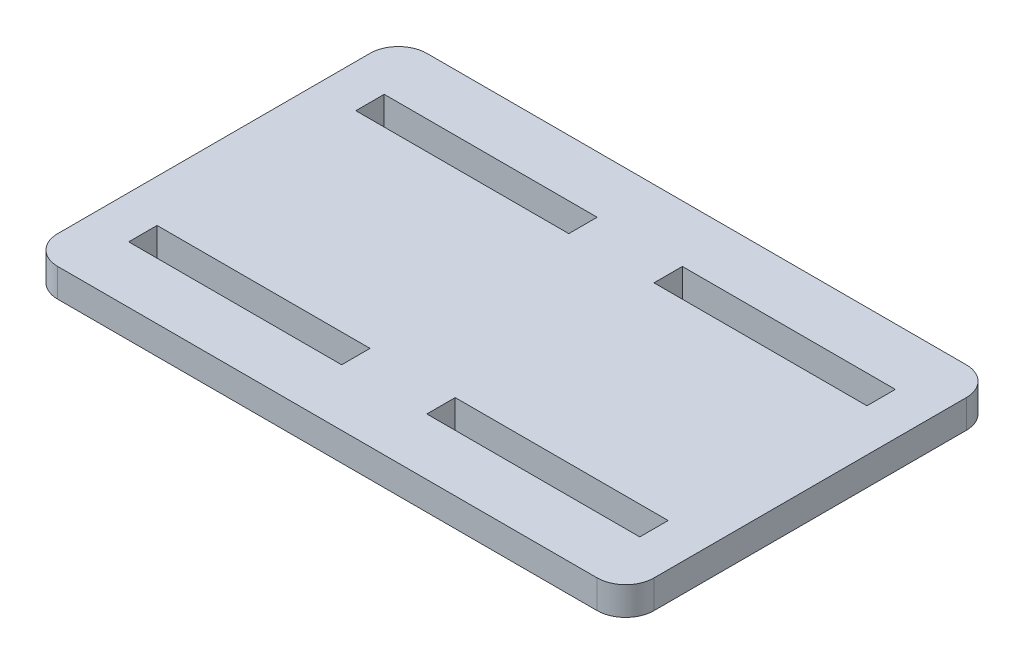
SolidWorks part; units mm, degrees
ref_plane "Front Plane" through (0, 0, 0) normal (0, 0, 1) x (1, 0, 0)
ref_plane "Top Plane" through (0, 0, 0) normal (0, 1, 0) x (1, 0, 0)
ref_plane "Right Plane" through (0, 0, 0) normal (1, 0, 0) x (0, 0, -1)
sketch "Sketch1" plane through (0, 0, 0) normal (1, 0, 0) x (0, 0, -1)
  line L0 (8.89, 0) -> (8.89, 2.54)
  line L1 (-8.89, 0) -> (-8.89, 2.54)
  line L2 (-8.89, 2.54) -> (8.89, 2.54)
  line L3 (-8.89, 0) -> (8.89, 0)
  point P0 (0, 0)
  dimension "D1" = 17.78
  dimension "D2" = 2.54
  dimension "D3" = 2.54
extrude "Boss-Extrude1" add sketch "Sketch1" along normal blind 11.43 contours L1 L3 L0 L2
sketch "Sketch2" plane through (0, 0, 0) normal (-1, 0, 0) x (0, 0, 1)
  line L0 (8.89, 0) -> (8.89, 2.54) construction
  line L1 (-8.89, 2.54) -> (8.89, 2.54)
  line L2 (-8.89, 2.54) -> (-8.89, 0)
  line L3 (-8.89, 0) -> (8.89, 0)
  line L4 (8.89, 2.54) -> (8.89, 0)
  dimension "D1" = 2.54
extrude "Boss-Extrude2" add sketch "Sketch2" along normal blind 15.24
mirror "Mirror1" about plane through (-15.24, 0, 0) normal (-1, 0, 0) of bodies 102 103
ref_plane "Plane1" through (11.43, 2.54, 8.89) normal (-1, 0, 0) x (0, 0, 1)
sketch "Sketch6" plane through (0, 0, -8.89) normal (0, 0, -1) x (-1, 0, 0)
  line L0 (41.91, 0) -> (41.91, 2.54) construction
  line L1 (-11.43, 2.54) -> (41.91, 2.54)
  line L2 (-11.43, 2.54) -> (-11.43, 0)
  line L3 (-11.43, 0) -> (41.91, 0)
  line L4 (41.91, 2.54) -> (41.91, 0)
  dimension "D1" = 2.54
sketch "Sketch7" plane through (0, 0, 8.89) normal (0, 0, 1) x (1, 0, 0)
  line L0 (11.43, 17.2085) -> (11.43, -12.1285) construction
  line L1 (-41.91, 2.54) -> (11.43, 2.54)
  line L2 (-41.91, 2.54) -> (-41.91, 0)
  line L3 (-41.91, 0) -> (11.43, 0)
  line L4 (11.43, 2.54) -> (11.43, 0)
  dimension "D1" = 2.54
ref_plane "Plane2" through (-15.24, 0, 0) normal (-1, 0, 0) x (0, 0, 1)
sketch "Sketch16" plane through (0, 0, 8.89) normal (0, 0, 1) x (1, 0, 0)
  line L0 (11.43, 0) -> (-41.91, 0) construction
  line L1 (-41.91, 2.54) -> (-38.1, 2.54)
  line L2 (-41.91, 2.54) -> (-41.91, 0)
  line L3 (-41.91, 0) -> (-38.1, 0)
  line L4 (-38.1, 2.54) -> (-38.1, 0)
  line L5 (11.43, 2.54) -> (-41.91, 2.54) construction
  line L6 (-15.24, 0) -> (-19.05, 0)
  line L7 (-15.24, 0) -> (-15.24, 2.54)
  line L8 (-15.24, 2.54) -> (-19.05, 2.54)
  line L9 (-19.05, 0) -> (-19.05, 2.54)
  line M3 (11.43, 2.54) -> (-41.91, 2.54)
  line M5 (-41.91, 0) -> (11.43, 0)
  dimension "D1" = 3.81
  dimension "D2" = 3.81
extrude "Boss-Extrude10" add sketch "Sketch16" along normal blind 7.62 contours L9 L7 M5 M3 | L4 L3 L2 L1
sketch "Sketch17" plane through (-19.05, 0, 0) normal (-1, 0, 0) x (0, 0, 1)
  line L0 (16.51, 2.54) -> (8.89, 2.54) construction
  line L1 (16.51, 0) -> (11.43, 0)
  line L2 (16.51, 0) -> (16.51, 2.54)
  line L3 (16.51, 2.54) -> (11.43, 2.54)
  line L4 (11.43, 0) -> (11.43, 2.54)
  dimension "D1" = 5.08
extrude "Boss-Extrude11" add sketch "Sketch17" along normal up to next
mirror "Mirror2" about plane through (-15.24, 0, 0) normal (-1, 0, 0) of "Boss-Extrude11", "Boss-Extrude10"
mirror "Mirror3" about plane through (0, 0, 0) normal (0, 0, 1) of "Mirror2", "Boss-Extrude11", "Boss-Extrude10"
sketch "Sketch18" plane through (0, 0, 0) normal (0, -1, 0) x (1, 0, 0)
  line L1 (-15.24, 8.89) -> (-10.2235, 8.89)
  line L2 (-15.24, 8.89) -> (-15.24, -8.89)
  line L3 (-15.24, -8.89) -> (-10.2235, -8.89)
  line L4 (-10.2235, 8.89) -> (-10.2235, -8.89)
  line L5 (11.43, -8.89) -> (-41.91, -8.89) construction
  line L7 (-15.24, 1.397) -> (-15.24, -1.397) construction
  dimension "D1" = 5.0165
  dimension "D2" = 17.78
fillet "Fillet1" radius 2.54 4 edges at (-41.91, 1.27, -16.51) (11.43, 1.27, -16.51) (-41.91, 1.27, 16.51) (11.43, 1.27, 16.51)
extrude "Boss-Extrude12" add sketch "Sketch18" along normal blind 5.0165 contours L4 L3 L2 L1
sketch "Sketch19" plane through (-10.2235, 0, 0) normal (1, 0, 0) x (0, 0, -1)
  line L0 (8.89, -5.0165) -> (8.89, 0) construction
  line L1 (-8.89, -5.0165) -> (8.89, -5.0165)
  line L2 (-8.89, -5.0165) -> (-8.89, -2.54)
  line L3 (-8.89, -2.54) -> (8.89, -2.54)
  line L4 (8.89, -5.0165) -> (8.89, -2.54)
  dimension "D1" = 2.4765
extrude "Boss-Extrude13" add sketch "Sketch19" along normal blind 5.0165
mirror "Mirror4" about plane through (-15.24, 0, 0) normal (-1, 0, 0) of "Boss-Extrude13", "Boss-Extrude12"
